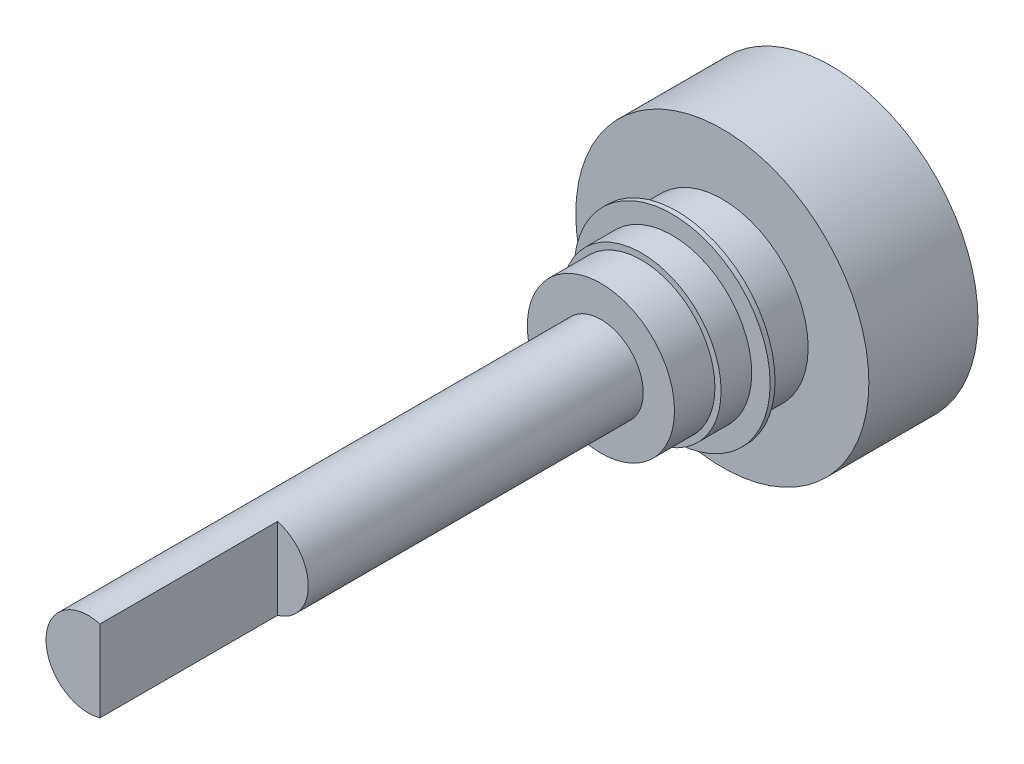
SolidWorks part; units mm, degrees
ref_plane "Front Plane" through (0, 0, 0) normal (1, 0, 0) x (0, 1, 0)
ref_plane "Top Plane" through (0, 0, 0) normal (0, 0, 1) x (0, 1, 0)
ref_plane "Right Plane" through (0, 0, 0) normal (0, 1, 0) x (-1, 0, 0)
sketch "Sketch2" plane through (0, 0, 0) normal (0, 0, 1) x (0, 1, 0)
  circle A0 centre (0, 0) radius 11.95
  dimension "D1" = 23.9
extrude "Boss-Extrude1" add sketch "Sketch2" along normal blind 8.9
sketch "Sketch3" plane through (0, 0, 8.9) normal (0, 0, 1) x (1, 0, 0)
  circle A0 centre (0, 0) radius 7
  dimension "D1" = 14
extrude "Boss-Extrude2" add sketch "Sketch3" along normal blind 3.7
sketch "Sketch5" plane through (0, 0, 12.6) normal (0, 0, 1) x (1, 0, 0)
  circle A0 centre (0, 0) radius 8
  dimension "D1" = 16
extrude "Boss-Extrude3" add sketch "Sketch5" along normal blind 0.4 contours A0
sketch "Sketch6" plane through (0, 0, 13) normal (0, 0, 1) x (1, 0, 0)
  circle A0 centre (0, 0) radius 6.5
  dimension "D1" = 13
extrude "Boss-Extrude4" add sketch "Sketch6" along normal blind 2.5
sketch "Sketch7" plane through (0, 0, 15.5) normal (0, 0, 1) x (1, 0, 0)
  circle A0 centre (0, 0) radius 6
  dimension "12" = 12
extrude "Boss-Extrude5" add sketch "Sketch7" along normal blind 3.3
sketch "Sketch8" plane through (0, 0, 18.8) normal (0, 0, 1) x (1, 0, 0)
  circle A0 centre (0, 0) radius 3.45
  dimension "D1" = 6.9
extrude "Boss-Extrude6" add sketch "Sketch8" along normal blind 41.8
sketch "Sketch9" plane through (0, 0, 60.6) normal (0, 0, 1) x (1, 0, 0)
  line L0 (-3.45, 0) -> (0.95, 0)
  line L1 (13.145, 0) -> (-13.145, 0) construction
  line L2 (0.95, -3.3166) -> (0.95, 3.3166)
  circle A0 centre (0, 0) radius 3.45 construction
  circle A1 centre (0, 0) radius 3.45 construction
  arc A2 (0.95, -3.3166) -> (0.95, 3.3166) centre (0, 0) ccw
  dimension "D1" = 4.4
sketch "Sketch10" plane through (0, 0, 60.6) normal (0, 0, 1) x (1, 0, 0)
  line L1 (0.95, 3.3166) -> (0.95, -3.3166)
  arc A0 (0.95, -3.3166) -> (0.95, 3.3166) centre (0, 0) ccw
  arc A1 (0.95, -3.3166) -> (0.95, 3.3166) centre (0, 0) ccw construction
extrude "Cut-Extrude2" cut sketch "Sketch10" against normal blind 14.49
